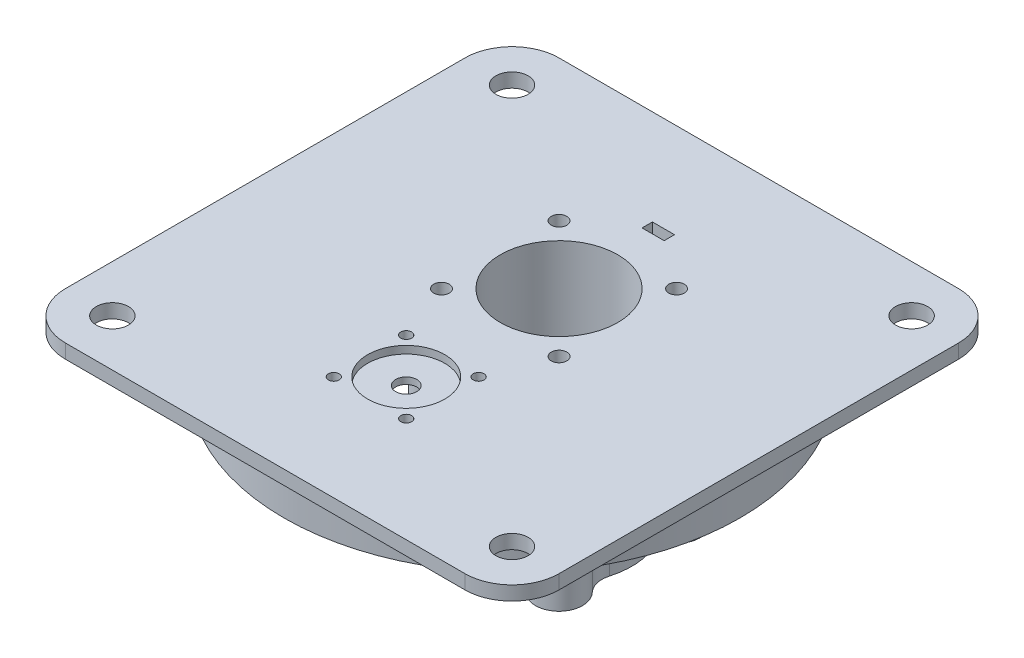
SolidWorks part; units mm, degrees
ref_plane "Front Plane" through (0, 0, 0) normal (0, 0, 1) x (1, 0, 0)
ref_plane "Top Plane" through (0, 0, 0) normal (0, 1, 0) x (1, 0, 0)
ref_plane "Right Plane" through (0, 0, 0) normal (1, 0, 0) x (0, 0, -1)
sketch "Sketch1" plane through (0, 0, 0) normal (0, 1, 0) x (1, 0, 0)
  line L1 (52.5, 52.5) -> (-52.5, 52.5)
  line L2 (52.5, 52.5) -> (52.5, -52.5)
  line L3 (52.5, -52.5) -> (-52.5, -52.5)
  line L4 (-52.5, 52.5) -> (-52.5, -52.5)
  line L5 (52.5, 52.5) -> (-52.5, -52.5) construction
  line L6 (52.5, -52.5) -> (-52.5, 52.5) construction
  point P0 (0, 0)
  dimension "D1" = 105
extrude "Boss-Extrude1" add sketch "Sketch1" along normal blind 3
sketch "Sketch3" plane through (0, 3, 0) normal (0, 1, 0) x (1, 0, 0)
  line L0 (0, 0) -> (0, -22.5) construction
  line L2 (7.7, -14.8) -> (-7.7, -14.8) construction
  line L3 (7.7, -14.8) -> (7.7, -30.2) construction
  line L4 (7.7, -30.2) -> (-7.7, -30.2) construction
  line L5 (-7.7, -14.8) -> (-7.7, -30.2) construction
  line L6 (7.7, -14.8) -> (-7.7, -30.2) construction
  line L7 (7.7, -30.2) -> (-7.7, -14.8) construction
  circle A0 centre (-7.7, -30.2) radius 1.15
  circle A1 centre (7.7, -30.2) radius 1.15
  circle A2 centre (7.7, -14.8) radius 1.15
  circle A3 centre (-7.7, -14.8) radius 1.15
  circle A4 centre (0, -22.5) radius 2.25
  dimension "D3" = 2.3
  dimension "D4" = 4.5
  dimension "D1" = 22.5
  dimension "D2" = 15.4
extrude "Cut-Extrude1" cut sketch "Sketch3" against normal through all
sketch "Sketch4" plane through (0, 3, 0) normal (0, 1, 0) x (1, 0, 0)
  circle A0 centre (0, -22.5) radius 8.2
  dimension "D1" = 16.4
extrude "Cut-Extrude2" cut sketch "Sketch4" against normal blind 1.6
sketch "Sketch5" plane through (0, 0, 0) normal (0, -1, 0) x (1, 0, 0)
  circle A0 centre (0, 0) radius 45.5
  circle A1 centre (0, 0) radius 48.5
  dimension "D1" = 91
  dimension "D2" = 3
extrude "Boss-Extrude3" add sketch "Sketch5" along normal blind 10
sketch "Sketch6" plane through (0, 0, 0) normal (0, -1, 0) x (1, 0, 0)
  line L0 (0, 0) -> (0, -35) construction
  circle A0 centre (0, 0) radius 35 construction
  circle A1 centre (0, -10) radius 12.5
  dimension "D1" = 70
  dimension "D3" = 25
  dimension "D2" = 10
extrude "Cut-Extrude3" cut sketch "Sketch6" against normal through all
sketch "Sketch7" plane through (0, 0, 0) normal (0, -1, 0) x (1, 0, 0)
  line L1 (12.5, -22.5) -> (-12.5, -22.5) construction
  line L2 (12.5, -22.5) -> (12.5, 2.5) construction
  line L3 (12.5, 2.5) -> (-12.5, 2.5) construction
  line L4 (-12.5, -22.5) -> (-12.5, 2.5) construction
  line L5 (12.5, -22.5) -> (-12.5, 2.5) construction
  line L6 (12.5, 2.5) -> (-12.5, -22.5) construction
  line L7 (10.15, 12.35) -> (-10.15, 12.35) construction
  line L8 (10.15, 12.35) -> (10.15, 32.65) construction
  line L9 (10.15, 32.65) -> (-10.15, 32.65) construction
  line L10 (-10.15, 12.35) -> (-10.15, 32.65) construction
  line L11 (10.15, 12.35) -> (-10.15, 32.65) construction
  line L12 (10.15, 32.65) -> (-10.15, 12.35) construction
  circle A0 centre (0, -10) radius 12.5 construction
  circle A1 centre (0, -10) radius 12.5
  circle A2 centre (-12.5, 2.5) radius 2.15 construction
  arc A3 (-7.6025, 3.5075) -> (-13.5075, -2.3975) centre (-12.5, 2.5) ccw
  arc A4 (13.5075, -2.3975) -> (7.6025, 3.5075) centre (12.5, 2.5) ccw
  arc A5 (7.6025, -23.5075) -> (13.5075, -17.6025) centre (12.5, -22.5) ccw
  arc A6 (-13.5075, -17.6025) -> (-7.6025, -23.5075) centre (-12.5, -22.5) ccw
  arc A7 (-13.5075, -2.3975) -> (-13.5075, -17.6025) centre (0, -10) ccw
  arc A8 (-7.6025, -23.5075) -> (7.6025, -23.5075) centre (0, -10) ccw
  arc A9 (13.5075, -17.6025) -> (13.5075, -2.3975) centre (0, -10) ccw
  arc A10 (7.6025, 3.5075) -> (-7.6025, 3.5075) centre (0, -10) ccw
  point P18 (0, 22.5)
  dimension "D2" = 4.3
  dimension "D3" = 10
  dimension "D4" = 3
  dimension "D1" = 25
  dimension "D5" = 20.3
extrude "Boss-Extrude4" add sketch "Sketch7" along normal blind 40.4
fillet "Fillet1" radius 5 8 edges at (-7.6025, -20.2, -23.5075) (-13.5075, -20.2, -17.6025) (13.5075, -20.2, -2.3975) (7.6025, -20.2, 3.5075) (-13.5075, -20.2, -2.3975) (7.6025, -20.2, -23.5075) (13.5075, -20.2, -17.6025) (-7.6025, -20.2, 3.5075)
sketch "Sketch8" plane through (0, -40.4, 0) normal (0, -1, 0) x (1, 0, 0)
  circle A0 centre (-12.5, -22.5) radius 2.15
  circle A1 centre (12.5, -22.5) radius 2.15
  circle A2 centre (-12.5, 2.5) radius 2.15
  circle A3 centre (12.5, 2.5) radius 2.15
  dimension "D1" = 4.3
extrude "Cut-Extrude4" cut sketch "Sketch8" against normal blind 10
sketch "Sketch9" plane through (0, -30.4, 0) normal (0, -1, 0) x (1, 0, 0)
  circle A0 centre (12.5, -22.5) radius 1.65
  circle A1 centre (-12.5, -22.5) radius 1.65
  circle A2 centre (-12.5, 2.5) radius 1.65
  circle A3 centre (12.5, 2.5) radius 1.65
  dimension "D1" = 3.3
extrude "Cut-Extrude5" cut sketch "Sketch9" against normal through all
fillet "Fillet2" radius 10 4 edges at (-52.5, 1.5, -52.5) (52.5, 1.5, -52.5) (52.5, 1.5, 52.5) (-52.5, 1.5, 52.5)
sketch "Sketch10" plane through (0, 0, 0) normal (0, -1, 0) x (1, 0, 0)
  circle A0 centre (-42.5, -42.5) radius 3.4195
  circle A1 centre (42.5, -42.5) radius 3.4195
  circle A2 centre (42.5, 42.5) radius 3.4195
  circle A3 centre (-42.5, 42.5) radius 3.4195
  dimension "D1" = 6.839
extrude "Cut-Extrude6" cut sketch "Sketch10" against normal through all
sketch "Sketch11" plane through (0, 0, 0) normal (0, -1, 0) x (1, 0, 0)
  line L0 (0, 0) -> (0, -31.1165) construction
  line L1 (2.35, -32.2165) -> (-2.35, -32.2165)
  line L2 (2.35, -32.2165) -> (2.35, -30.0165)
  line L3 (2.35, -30.0165) -> (-2.35, -30.0165)
  line L4 (-2.35, -32.2165) -> (-2.35, -30.0165)
  line L5 (2.35, -32.2165) -> (-2.35, -30.0165) construction
  line L6 (2.35, -30.0165) -> (-2.35, -32.2165) construction
  line L7 (3.55, -33.4165) -> (-3.55, -33.4165)
  line L8 (-3.55, -33.4165) -> (-3.55, -28.8165)
  line L9 (3.55, -28.8165) -> (-3.55, -28.8165)
  line L10 (3.55, -33.4165) -> (3.55, -28.8165)
  point P0 (0, -31.1165)
  dimension "D2" = 4.7
  dimension "D3" = 2.2
  dimension "D1" = 1.2
extrude "Boss-Extrude5" add sketch "Sketch11" along normal blind 5.7
sketch "Sketch12" plane through (0, -5.7, 0) normal (0, -1, 0) x (1, 0, 0)
  line L1 (3.55, -33.4165) -> (-3.55, -33.4165)
  line L2 (3.55, -33.4165) -> (3.55, -28.8165)
  line L3 (3.55, -28.8165) -> (-3.55, -28.8165)
  line L4 (-3.55, -33.4165) -> (-3.55, -28.8165)
extrude "Boss-Extrude6" add sketch "Sketch12" along normal blind 1
sketch "Sketch13" plane through (0, 0, 0) normal (0, -1, 0) x (1, 0, 0)
  line L0 (2.35, -32.2165) -> (2.35, -30.0165) construction
  line L1 (2.35, -30.0165) -> (-2.35, -30.0165) construction
  line L2 (-2.35, -32.2165) -> (-2.35, -30.0165) construction
  line L3 (2.35, -32.2165) -> (-2.35, -32.2165) construction
  line L4 (2.35, -32.2165) -> (2.35, -30.0165)
  line L5 (2.35, -30.0165) -> (-2.35, -30.0165)
  line L6 (-2.35, -32.2165) -> (-2.35, -30.0165)
  line L7 (2.35, -32.2165) -> (-2.35, -32.2165)
extrude "Cut-Extrude7" cut sketch "Sketch13" against normal up to surface (3 mm away) up to face at (-42.5, 3, 39.0805)
